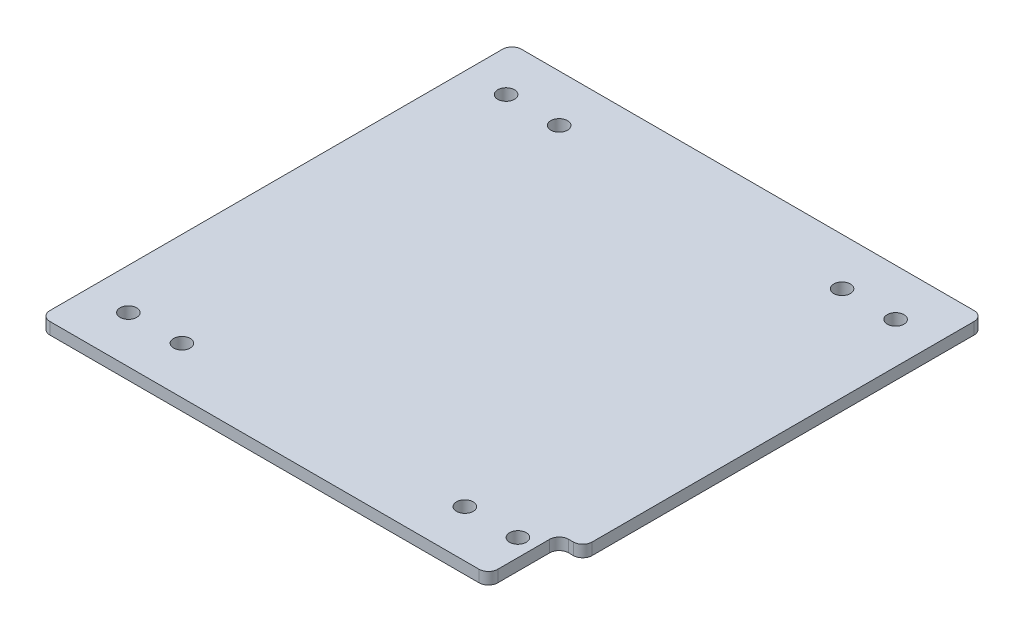
SolidWorks part; units mm, degrees
material "Acrylic (Medium-high impact)"
ref_plane "Front Plane" through (0, 0, 0) normal (0, 0, 1) x (1, 0, 0)
ref_plane "Top Plane" through (0, 0, 0) normal (0, 1, 0) x (1, 0, 0)
ref_plane "Right Plane" through (0, 0, 0) normal (1, 0, 0) x (0, 0, -1)
sketch "Sketch1" plane through (0, 0, 0) normal (0, 1, 0) x (1, 0, 0)
  line L1 (-105.3264, 76.506) -> (21.6736, 76.506)
  line L2 (-105.3264, 76.506) -> (-105.3264, -50.494)
  line L3 (-105.3264, -50.494) -> (21.6736, -50.494)
  line L4 (21.6736, 76.506) -> (21.6736, -50.494)
  line L5 (-105.3264, 76.506) -> (21.6736, -50.494) construction
  line L6 (-105.3264, -50.494) -> (21.6736, 76.506) construction
  point P0 (-41.8264, 13.006)
  dimension "D1" = 127
  dimension "D2" = 127
extrude "Boss-Extrude1" add sketch "Sketch1" along normal blind 3.175
hole_wizard "#16 (0.177) Diameter Hole1" positions "Sketch8" profile "Sketch9" hole size "#16" standard "ANSI Inch" end condition through all
sketch "Sketch8" plane through (0, 0, 0) normal (0, -1, 0) x (-1, 0, 0)
  line L0 (-21.6736, -50.494) -> (105.3264, 76.506) construction
  line L3 (79.9264, -37.794) -> (3.7264, -37.794) construction
  line L4 (79.9264, -37.794) -> (79.9264, 63.806) construction
  line L5 (79.9264, 63.806) -> (3.7264, 63.806) construction
  line L6 (3.7264, -37.794) -> (3.7264, 63.806) construction
  line L7 (79.9264, -37.794) -> (3.7264, 63.806) construction
  line L8 (79.9264, 63.806) -> (3.7264, -37.794) construction
  point P6 (3.7264, 63.806)
  point P53 (79.9264, -37.794)
  point P54 (79.9264, 63.806)
  point P55 (3.7264, -37.794)
  dimension "D1" = 76.2
  dimension "D2" = 101.6
sketch "Sketch9" plane through (-3.7264, 0, -63.806) normal (1, 0, 0) x (0, 0, -1)
  line L0 (0, 0) -> (0, 3.175)
  line L1 (0, 3.175) -> (2.2479, 3.175)
  line L2 (2.2479, 3.175) -> (2.2479, 0)
  line L5 (2.2479, 0) -> (0, 0)
  line L11 (0, -6.35) -> (0, 107.95) construction
  dimension "Thru Hole Dia." = 4.4958
  dimension "Thru Hole Depth" = 3.175
hole_wizard "#16 (0.177) Diameter Hole2" positions "Sketch10" profile "Sketch11" hole size "#16" standard "ANSI Inch" end condition through all
sketch "Sketch10" plane through (0, 0, 0) normal (0, -1, 0) x (-1, 0, 0)
  line L21 (94.2774, -37.8575) -> (-10.6246, -37.8575) construction
  line L22 (94.2774, -37.8575) -> (94.2774, 63.8695) construction
  line L23 (94.2774, 63.8695) -> (-10.6246, 63.8695) construction
  line L24 (-10.6246, -37.8575) -> (-10.6246, 63.8695) construction
  line L25 (94.2774, -37.8575) -> (-10.6246, 63.8695) construction
  line L26 (94.2774, 63.8695) -> (-10.6246, -37.8575) construction
  line L27 (41.8264, -50.494) -> (41.8264, 13.006) construction
  line L28 (105.3264, -50.494) -> (-21.6736, -50.494) construction
  line L29 (41.8264, 13.006) -> (105.3264, 13.006) construction
  line L30 (105.3264, 76.506) -> (105.3264, -50.494) construction
  point P152 (-10.6246, 63.8695)
  point P223 (94.2774, -37.8575)
  point P224 (94.2774, 63.8695)
  point P225 (-10.6246, -37.8575)
  dimension "D1" = 104.902
  dimension "D2" = 101.727
sketch "Sketch11" plane through (10.6246, 0, -63.8695) normal (1, 0, 0) x (0, 0, -1)
  line L0 (0, 0) -> (0, 3.175)
  line L1 (0, 3.175) -> (2.2479, 3.175)
  line L2 (2.2479, 3.175) -> (2.2479, 0)
  line L5 (2.2479, 0) -> (0, 0)
  line L11 (0, -6.35) -> (0, 107.95) construction
  dimension "Thru Hole Dia." = 4.4958
  dimension "Thru Hole Depth" = 3.175
sketch "Sketch12" plane through (0, 3.175, 0) normal (0, 1, 0) x (1, 0, 0)
  line L1 (-105.3264, -50.494) -> (21.6736, -50.494) construction
  line L2 (15.3236, -50.494) -> (21.6736, -50.494)
  line L3 (15.3236, -50.494) -> (15.3236, -31.444)
  line L4 (15.3236, -31.444) -> (21.6736, -31.444)
  line L6 (21.6736, -50.494) -> (21.6736, -31.444)
  line L7 (21.6736, -50.494) -> (21.6736, 76.506) construction
  dimension "D1" = 6.35
  dimension "D2" = 19.05
extrude "Cut-Extrude1" cut sketch "Sketch12" against normal through all
fillet "Fillet1" radius 2.54 6 edges at (-105.3264, 1.5875, 50.494) (21.6736, 1.5875, -76.506) (-105.3264, 1.5875, -76.506) (21.6736, 1.5875, 31.444) (15.3236, 1.5875, 31.444) (15.3236, 1.5875, 50.494)
